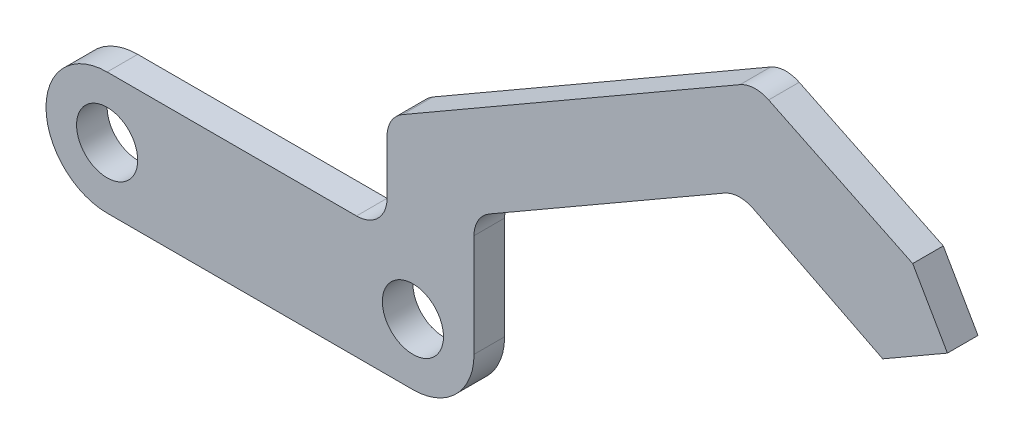
SolidWorks part; units mm, degrees
ref_plane "Front Plane" through (0, 0, 0) normal (0, 0, 1) x (1, 0, 0)
ref_plane "Top Plane" through (0, 0, 0) normal (0, 1, 0) x (1, 0, 0)
ref_plane "Right Plane" through (0, 0, 0) normal (1, 0, 0) x (0, 0, -1)
sketch "Sketch1" plane through (0, 0, 0) normal (0, 0, 1) x (1, 0, 0)
  line L0 (0, 0) -> (30.017, 0) construction
  line L1 (0, 6) -> (30.017, 6)
  line L2 (0, -6) -> (30.017, -6)
  line L3 (27.4785, 6) -> (30.017, 6) construction
  line L4 (27.4785, 6) -> (27.4785, 56) construction
  line L5 (30.017, 6) -> (30.017, 56) construction
  line L6 (27.4785, 56) -> (30.017, 56) construction
  line L7 (27.4785, 6) -> (27.4785, 16)
  line L8 (36.017, 0) -> (36.017, 11.822)
  line L9 (25.482, 56) -> (30.017, 56)
  line L10 (36.017, 11.822) -> (62.003, 26.8129)
  line L11 (62.003, 26.8129) -> (76.1385, 19.68)
  line L12 (76.1385, 19.68) -> (82.4875, 23.3426)
  line L13 (82.4875, 23.3426) -> (79.078, 29.2527)
  line L14 (63.5067, 36.7841) -> (79.078, 29.2527)
  line L15 (27.4785, 16) -> (63.5067, 36.7841)
  arc A0 (0, 6) -> (0, -6) centre (0, 0) ccw
  arc A1 (30.017, -6) -> (30.017, 6) centre (30.017, 0) ccw
  circle A2 centre (0, 0) radius 3
  circle A3 centre (30.017, 0) radius 3
  point P3 (15.0085, 0)
  point P15 (62.003, 24.721)
  point P25 (62.003, 24.721)
  point P26 (0, 0)
  point P28 (36.017, 9.7301)
  dimension "D1" = 90
  dimension "D9" = 13.242
  dimension "D6" = 119.98
  dimension "D2" = 30.017
  dimension "D3" = 2.5385
  dimension "D4" = 10
  dimension "D5" = 6.5149
  dimension "D7" = 50
  dimension "D8" = 30
extrude "Boss-Extrude1" add sketch "Sketch1" along normal blind 3
fillet "Fillet1" radius 3 1 edges at (27.4785, 16, 1.5)
fillet "Fillet2" radius 3 1 edges at (27.4785, 6, 1.5)
fillet "Fillet3" radius 3 3 edges at (36.017, 11.822, 1.5) (62.003, 26.8129, 1.5) (63.5067, 36.7841, 1.5)
